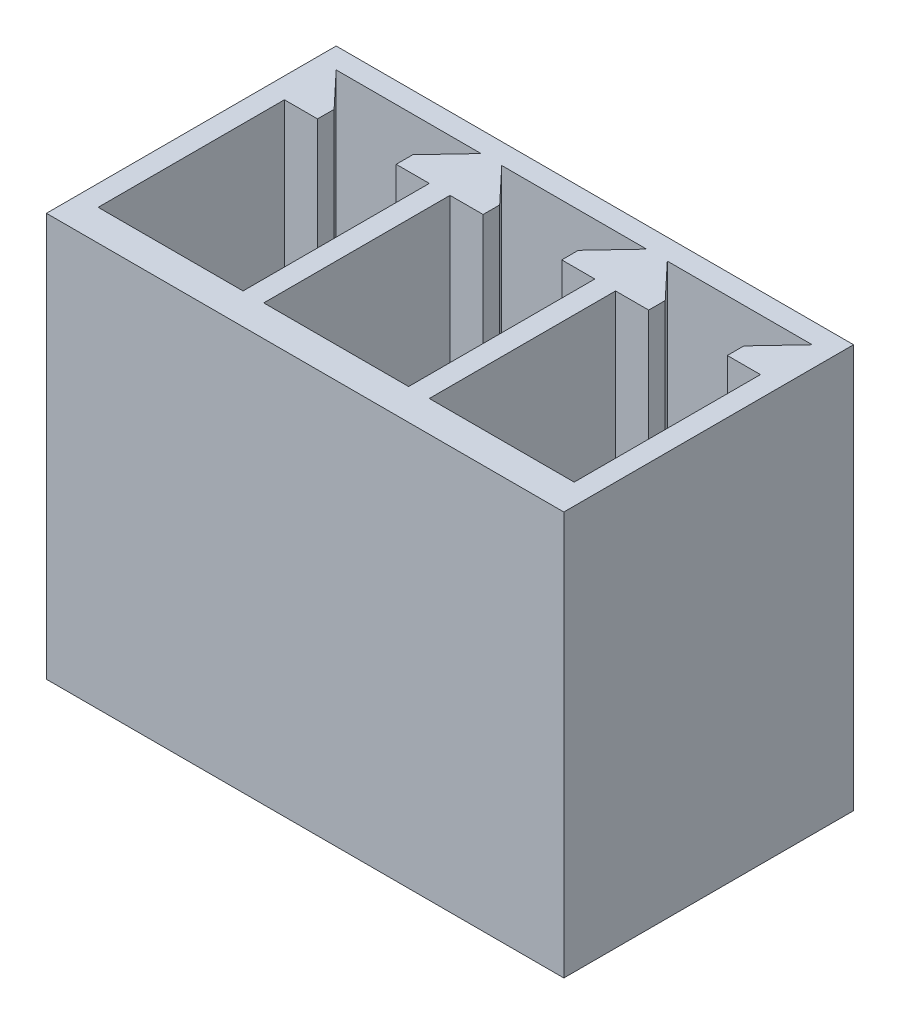
SolidWorks part; units mm, degrees
ref_plane "Front Plane" through (0, 0, 0) normal (0, 0, 1) x (1, 0, 0)
ref_plane "Top Plane" through (0, 0, 0) normal (0, 1, 0) x (1, 0, 0)
ref_plane "Right Plane" through (0, 0, 0) normal (1, 0, 0) x (0, 0, -1)
sketch "Sketch1" plane through (0, 0, 0) normal (0, 1, 0) x (1, 0, 0)
  line L0 (6.25, 0) -> (6.25, 7)
  line L1 (6.25, 7) -> (-6.25, 7)
  line L2 (-6.25, 7) -> (-6.25, 0)
  line L3 (-6.25, 0) -> (6.25, 0)
  line L4 (-5.75, 5.25) -> (-5.75, 0.75)
  line L5 (-5.75, 0.75) -> (-2.25, 0.75)
  line L6 (-2.25, 0.75) -> (-2.25, 5.25)
  line L7 (-2.25, 5.25) -> (-3.05, 5.25)
  line L8 (-3.05, 5.25) -> (-3.05, 5.65)
  line L9 (-3.05, 5.65) -> (-2.25, 6.5)
  line L10 (-2.25, 6.5) -> (-5.75, 6.5)
  line L11 (-5.75, 6.5) -> (-4.95, 5.65)
  line L12 (-4.95, 5.65) -> (-4.95, 5.25)
  line L13 (-4.95, 5.25) -> (-5.75, 5.25)
  line L14 (-1.75, 5.25) -> (-1.75, 0.75)
  line L15 (-1.75, 0.75) -> (1.75, 0.75)
  line L16 (1.75, 0.75) -> (1.75, 5.25)
  line L17 (1.75, 5.25) -> (0.95, 5.25)
  line L18 (0.95, 5.25) -> (0.95, 5.65)
  line L19 (0.95, 5.65) -> (1.75, 6.5)
  line L20 (1.75, 6.5) -> (-1.75, 6.5)
  line L21 (-1.75, 6.5) -> (-0.95, 5.65)
  line L22 (-0.95, 5.65) -> (-0.95, 5.25)
  line L23 (-0.95, 5.25) -> (-1.75, 5.25)
  line L24 (2.25, 5.25) -> (2.25, 0.75)
  line L25 (2.25, 0.75) -> (5.75, 0.75)
  line L26 (5.75, 0.75) -> (5.75, 5.25)
  line L27 (5.75, 5.25) -> (4.95, 5.25)
  line L28 (4.95, 5.25) -> (4.95, 5.65)
  line L29 (4.95, 5.65) -> (5.75, 6.5)
  line L30 (5.75, 6.5) -> (2.25, 6.5)
  line L31 (2.25, 6.5) -> (3.05, 5.65)
  line L32 (3.05, 5.65) -> (3.05, 5.25)
  line L33 (3.05, 5.25) -> (2.25, 5.25)
  dimension "D2" = 0.95
  dimension "D3" = 1.75
  dimension "D4" = 0.75
  dimension "D5" = 5.65
  dimension "D6" = 5.75
  dimension "D7" = 6.25
  dimension "D8" = 5.75
  dimension "D9" = 7
  dimension "D10" = 2.25
  dimension "D11" = 5.25
  dimension "D12" = 6.5
  dimension "D14" = 6.25
extrude "Boss-Extrude1" add sketch "Sketch1" along normal blind 9.25
sketch "Sketch2" plane through (0, 0, 0) normal (0, -1, 0) x (1, 0, 0)
  line L4 (6.25, 0) -> (-6.25, 0)
  line L5 (-6.25, 0) -> (-6.25, -7)
  line L6 (-6.25, -7) -> (6.25, -7)
  line L7 (6.25, -7) -> (6.25, 0)
  line L8 (6.25, 0) -> (-6.25, 0)
  line L9 (-6.25, 0) -> (-6.25, -7)
  line L10 (-6.25, -7) -> (6.25, -7)
  line L11 (6.25, -7) -> (6.25, 0)
  dimension "D1" = 0
extrude "Boss-Extrude2" add sketch "Sketch2" along normal blind 0.5
